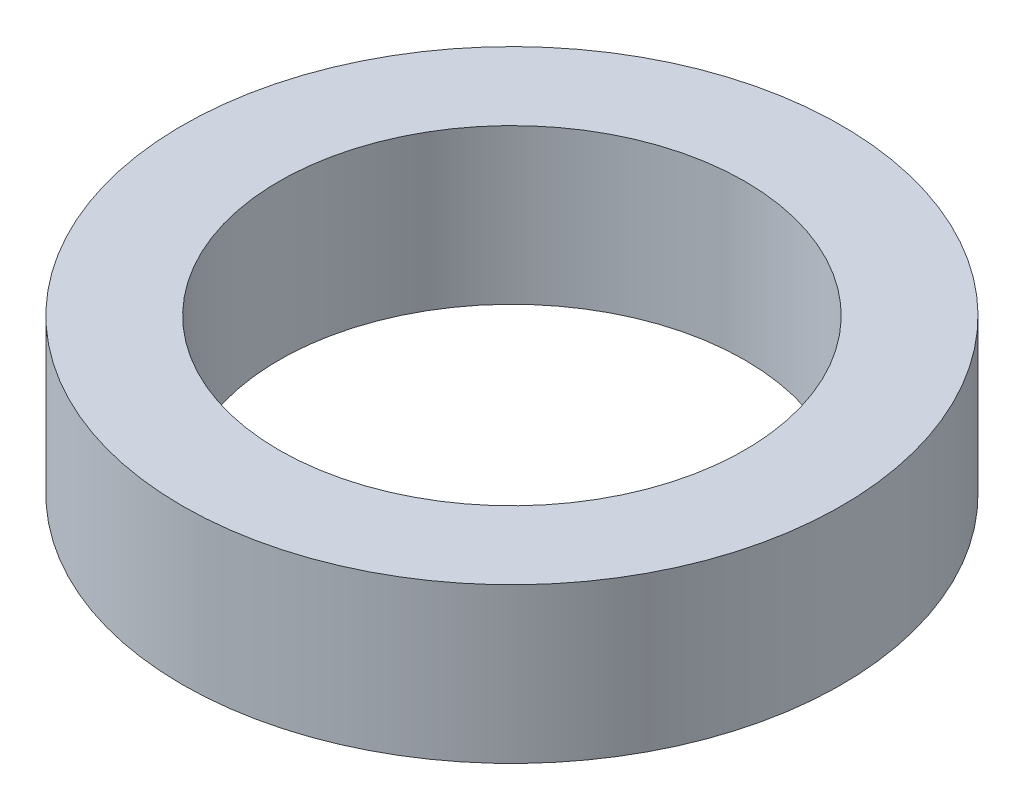
SolidWorks part; units mm, degrees
material "PP Copolymer"
ref_plane "Front Plane" through (0, 0, 0) normal (0, 0, 1) x (1, 0, 0)
ref_plane "Top Plane" through (0, 0, 0) normal (0, 1, 0) x (1, 0, 0)
ref_plane "Right Plane" through (0, 0, 0) normal (1, 0, 0) x (0, 0, -1)
sketch "Sketch2" plane through (0, 0, 0) normal (0, 1, 0) x (1, 0, 0)
  circle A0 centre (0, 0) radius 76.4286
  circle A1 centre (0, 0) radius 108.1786
  dimension "D1" = 152.8572
  dimension "D2" = 31.75
extrude "Boss-Extrude1" add sketch "Sketch2" along normal blind 50.8
equation "\"shoulder offset\"= 1.25"
equation "\"ID\"=5.998"
equation "\"L\" = 2"
equation "\"D1@Sketch2\"=\"ID\"+\"ID offset\""
equation "\"D2@Sketch2\"=\"shoulder offset\""
equation "\"D1@Boss-Extrude1\"=\"L\""
equation "\"ID offset\"= 0.02"
